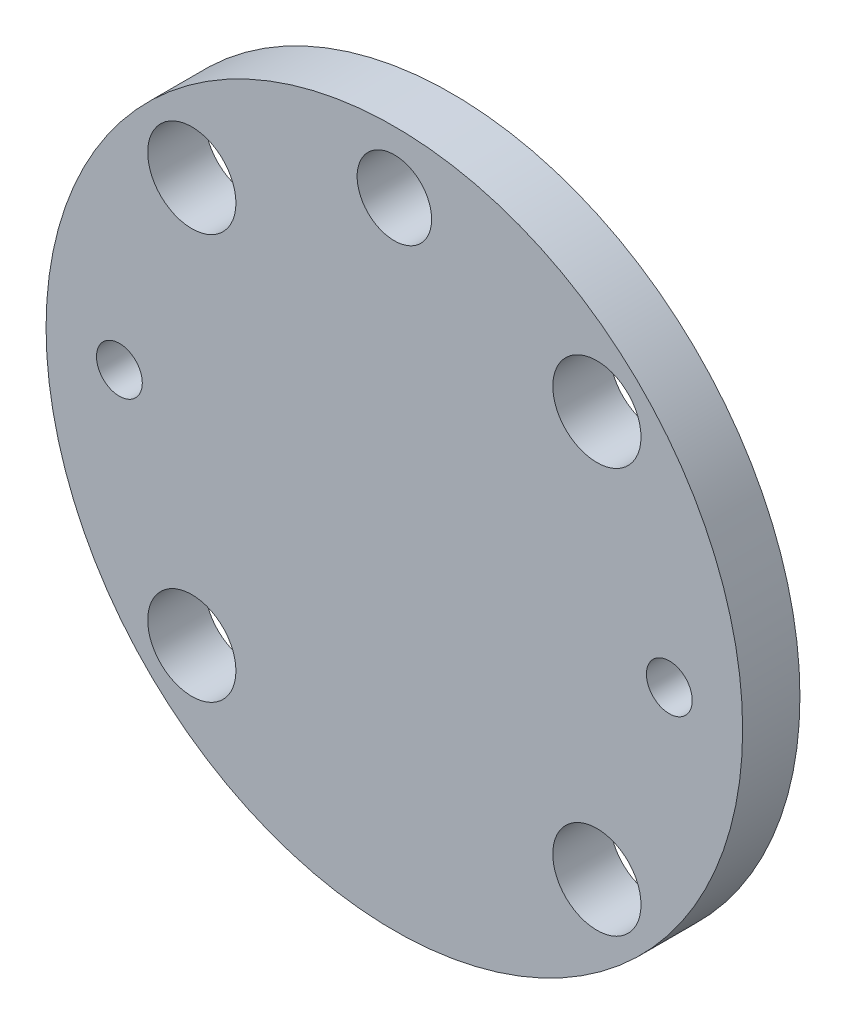
SolidWorks part; units mm, degrees
ref_plane "Front Plane" through (0, 0, 0) normal (0, 0, 1) x (1, 0, 0)
ref_plane "Top Plane" through (0, 0, 0) normal (0, 1, 0) x (1, 0, 0)
ref_plane "Right Plane" through (0, 0, 0) normal (1, 0, 0) x (0, 0, -1)
sketch "Sketch1" plane through (0, 0, 0) normal (0, 0, 1) x (1, 0, 0)
  line L0 (0, 0) -> (24, 0)
  line L1 (0, 30.4) -> (0, 0)
  circle A0 centre (0, 25) radius 3.25
  circle A1 centre (17.6777, 17.6777) radius 3.85
  circle A2 centre (17.6777, -17.6777) radius 3.85
  circle A3 centre (-17.6777, -17.6777) radius 3.85
  circle A4 centre (-17.6777, 17.6777) radius 3.85
  arc A5 (0, -30.4) -> (0, 30.4) centre (0, 0) ccw
  arc A6 (0, 30.4) -> (0, -30.4) centre (0, 0) ccw
  circle A7 centre (24, 0) radius 2
  circle A8 centre (-24, 0) radius 2
  point P18 (0, 0)
  dimension "D1" = 30.4
  dimension "D3" = 4
  dimension "D2" = 24
extrude "Boss-Extrude1" add sketch "Sketch1" along normal blind 5
